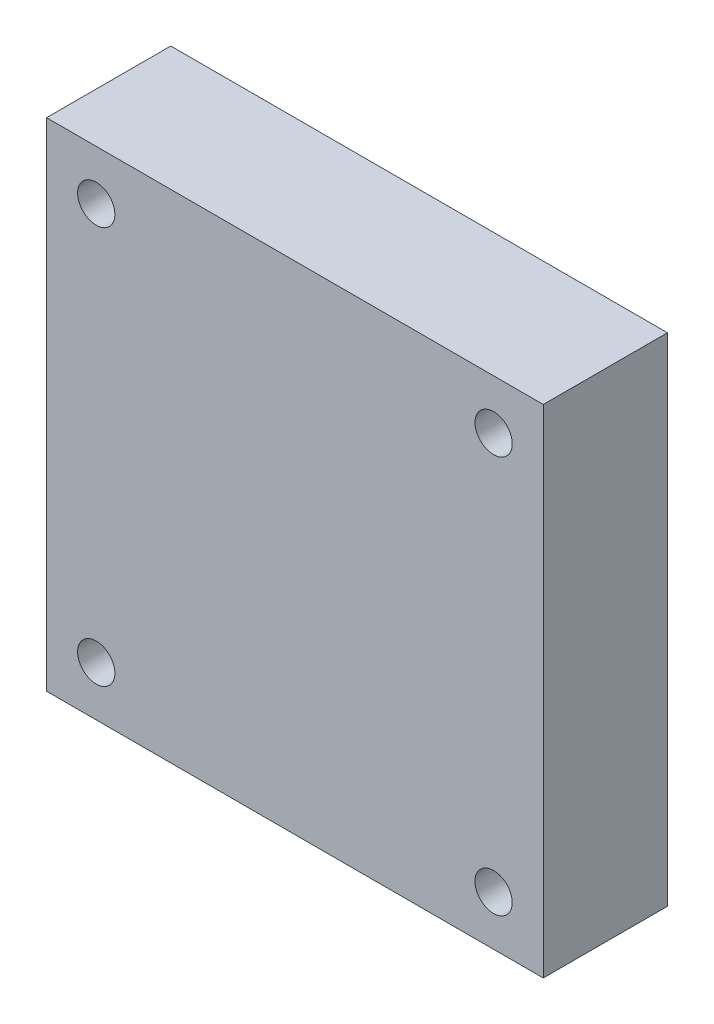
SolidWorks part; units mm, degrees
ref_plane "Plan de face" through (0, 0, 0) normal (0, 0, 1) x (1, 0, 0)
ref_plane "Plan de dessus" through (0, 0, 0) normal (0, 1, 0) x (1, 0, 0)
ref_plane "Plan de droite" through (0, 0, 0) normal (1, 0, 0) x (0, 0, -1)
sketch "Esquisse1" plane through (0, 0, 0) normal (0, 0, 1) x (1, 0, 0)
  line L0 (0, 20) -> (0, -20) construction
  line L1 (-20, -20) -> (20, -20)
  line L2 (-20, -20) -> (-20, 20)
  line L3 (-20, 20) -> (20, 20)
  line L4 (20, -20) -> (20, 20)
  line L5 (-20, 20) -> (0, 0) construction
  line L6 (20, 0) -> (-20, 0) construction
  circle A0 centre (-16, 16) radius 1.5
  circle A1 centre (16, 16) radius 1.5
  circle A2 centre (16, -16) radius 1.5
  circle A3 centre (-16, -16) radius 1.5
  dimension "D1" = 40
  dimension "D2" = 32
  dimension "D3" = 3
extrude "Boss.-Extru.1" add sketch "Esquisse1" along normal blind 10
